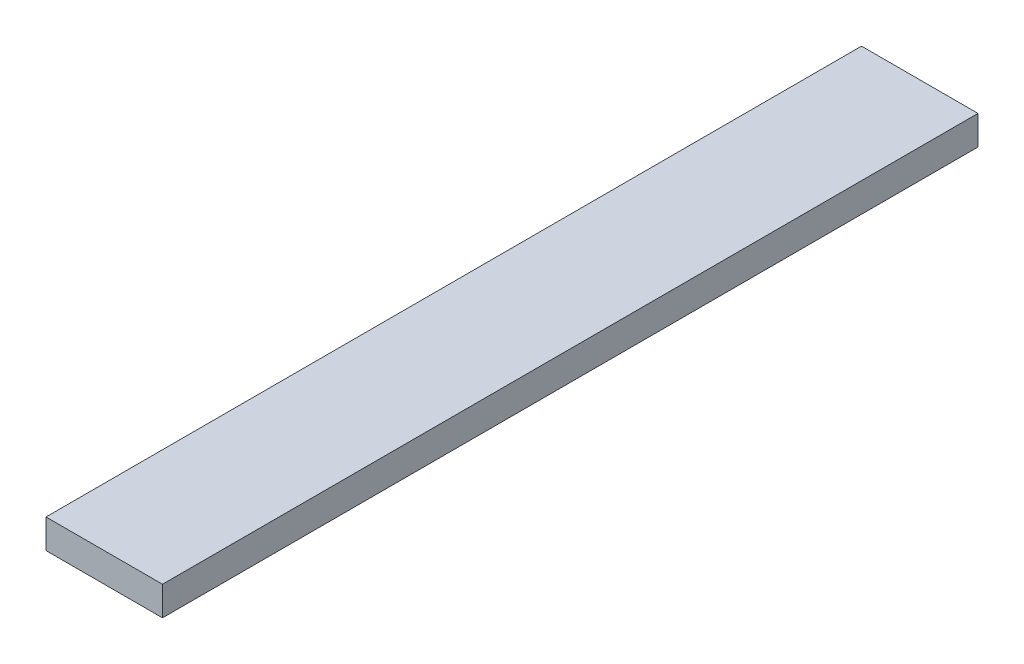
SolidWorks part; units mm, degrees
ref_plane "Front Plane" through (0, 0, 0) normal (0, 0, 1) x (1, 0, 0)
ref_plane "Top Plane" through (0, 0, 0) normal (0, 1, 0) x (1, 0, 0)
ref_plane "Right Plane" through (0, 0, 0) normal (1, 0, 0) x (0, 0, -1)
sketch "Sketch1" plane through (0, 0, 0) normal (0, 1, 0) x (1, 0, 0)
  line L1 (-12.7, -88.9) -> (12.7, -88.9)
  line L2 (-12.7, -88.9) -> (-12.7, 88.9)
  line L3 (-12.7, 88.9) -> (12.7, 88.9)
  line L4 (12.7, -88.9) -> (12.7, 88.9)
  line L5 (-12.7, -88.9) -> (12.7, 88.9) construction
  line L6 (-12.7, 88.9) -> (12.7, -88.9) construction
  point P0 (0, 0)
  dimension "D1" = 177.8
  dimension "D2" = 25.4
extrude "Boss-Extrude1" add sketch "Sketch1" along normal blind 6.35
